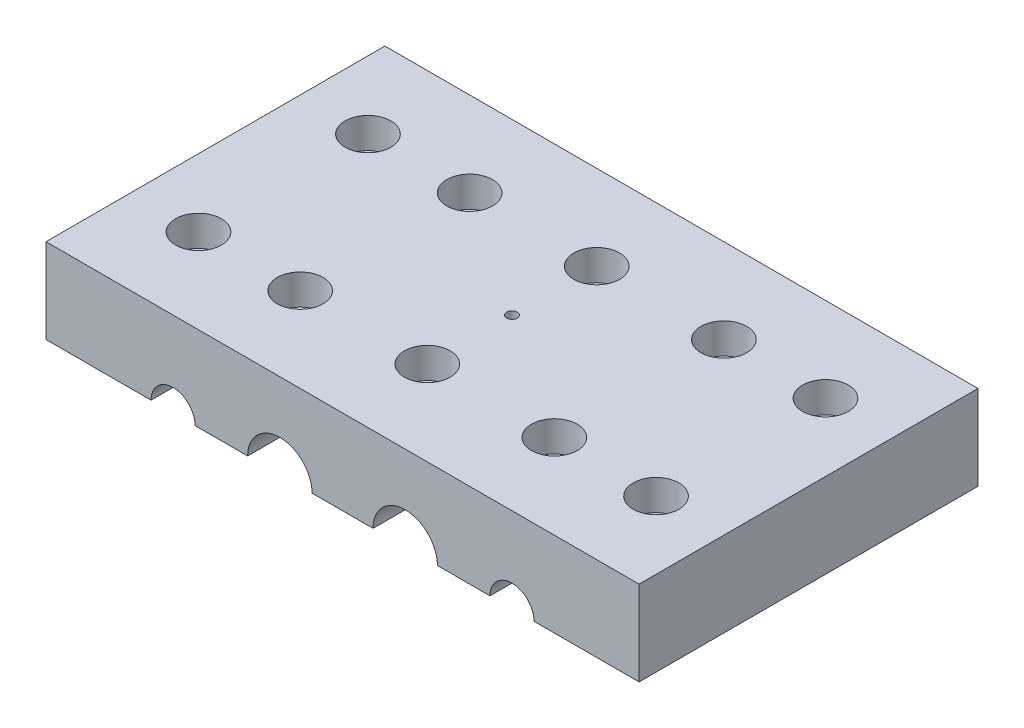
SolidWorks part; units mm, degrees
material "Copper"
ref_plane "Front Plane" through (0, 0, 0) normal (0, 0, 1) x (1, 0, 0)
ref_plane "Top Plane" through (0, 0, 0) normal (0, 1, 0) x (1, 0, 0)
ref_plane "Right Plane" through (0, 0, 0) normal (1, 0, 0) x (0, 0, -1)
sketch "Sketch1" plane through (0, 0, 0) normal (0, 1, 0) x (1, 0, 0)
  line L1 (-44.45, 25.4) -> (44.45, 25.4)
  line L2 (-44.45, 25.4) -> (-44.45, -25.4)
  line L3 (-44.45, -25.4) -> (44.45, -25.4)
  line L4 (44.45, 25.4) -> (44.45, -25.4)
  line L5 (-44.45, 25.4) -> (44.45, -25.4) construction
  line L6 (-44.45, -25.4) -> (44.45, 25.4) construction
  point P0 (0, 0)
  dimension "D1" = 88.9
  dimension "D2" = 50.8
extrude "Boss-Extrude1" add sketch "Sketch1" along normal blind 12.7
sketch "Sketch2" plane through (0, 12.7, 0) normal (0, 1, 0) x (1, 0, 0)
  line L0 (44.45, 25.4) -> (-44.45, 25.4) construction
  line L1 (-44.45, 25.4) -> (-44.45, -25.4) construction
  line L2 (44.45, -25.4) -> (44.45, 25.4) construction
  circle A0 centre (-34.29, 12.7) radius 3.429
  circle A1 centre (-19.05, 12.7) radius 3.429
  circle A2 centre (0, 12.7) radius 3.429
  circle A3 centre (19.05, 12.7) radius 3.429
  circle A4 centre (34.29, 12.7) radius 3.429
  circle A5 centre (-34.29, 12.7) radius 2.286
  circle A6 centre (-19.05, 12.7) radius 2.286
  circle A7 centre (0, 12.7) radius 2.286
  circle A8 centre (19.05, 12.7) radius 2.286
  circle A9 centre (34.29, 12.7) radius 2.286
  dimension "D1" = 4.572
  dimension "D2" = 4.572
  dimension "D3" = 4.572
  dimension "D4" = 4.572
  dimension "D5" = 4.572
  dimension "D6" = 6.858
  dimension "D7" = 6.858
  dimension "D8" = 6.858
  dimension "D9" = 6.858
  dimension "D10" = 6.858
  dimension "D11" = 12.7
  dimension "D12" = 12.7
  dimension "D13" = 12.7
  dimension "D14" = 12.7
  dimension "D15" = 12.7
  dimension "D16" = 10.16
  dimension "D17" = 25.4
  dimension "D18" = 44.45
  dimension "D19" = 25.4
  dimension "D20" = 10.16
extrude "Cut-Extrude1" cut sketch "Sketch2" against normal blind 4.572
sketch "Sketch3" plane through (0, 12.7, 0) normal (0, 1, 0) x (1, 0, 0)
  circle A0 centre (-34.29, 12.7) radius 2.286
  circle A1 centre (-19.05, 12.7) radius 2.286
  circle A2 centre (0, 12.7) radius 2.286
  circle A3 centre (19.05, 12.7) radius 2.286
  circle A4 centre (34.29, 12.7) radius 2.286
extrude "Cut-Extrude2" cut sketch "Sketch3" against normal through all
pattern_linear "LPattern1" count 2 spacing 25.4 along (0, 0, 1) of "Cut-Extrude1"
sketch "Sketch4" plane through (0, 0, 25.4) normal (0, 0, 1) x (1, 0, 0)
  line L0 (-44.45, 0) -> (44.45, 0) construction
  line L1 (-28.702, 0) -> (-22.098, 0)
  line L2 (-14.224, 0) -> (-4.572, 0)
  line L3 (4.572, 0) -> (14.224, 0)
  line L4 (22.098, 0) -> (28.702, 0)
  arc A0 (-22.098, 0) -> (-28.702, 0) centre (-25.4, 0) ccw
  arc A1 (-4.572, 0) -> (-14.224, 0) centre (-9.398, 0) ccw
  arc A2 (14.224, 0) -> (4.572, 0) centre (9.398, 0) ccw
  arc A3 (28.702, 0) -> (22.098, 0) centre (25.4, 0) ccw
  dimension "D1" = 3.302
  dimension "D2" = 9.144
  dimension "D4" = 4.826
  dimension "D5" = 4.826
  dimension "D6" = 3.302
  dimension "D3" = 7.874
  dimension "D8" = 7.874
extrude "Cut-Extrude3" cut sketch "Sketch4" against normal through all
sketch "Sketch5" plane through (0, 12.7, 0) normal (0, 1, 0) x (1, 0, 0)
  circle A0 centre (0, 0) radius 0.7874
  dimension "D1" = 1.5748
extrude "Cut-Extrude4" cut sketch "Sketch5" against normal through all
sketch "Sketch6" plane through (0, 12.7, 0) normal (0, 1, 0) x (1, 0, 0)
  circle A0 centre (-34.29, -12.7) radius 2.286
  circle A1 centre (-19.05, -12.7) radius 2.286
  circle A2 centre (0, -12.7) radius 2.286
  circle A3 centre (19.05, -12.7) radius 2.286
  circle A4 centre (34.29, -12.7) radius 2.286
extrude "Cut-Extrude5" cut sketch "Sketch6" against normal through all
